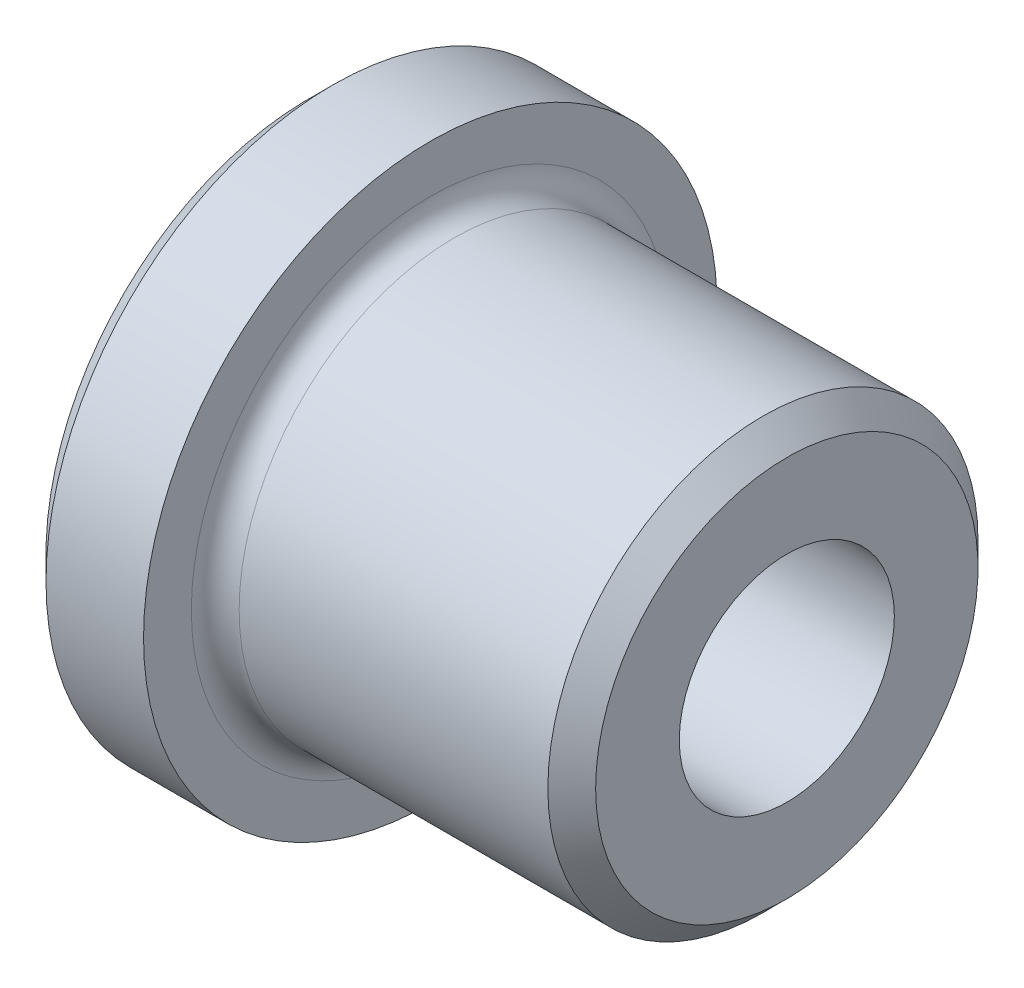
SolidWorks part; units mm, degrees
ref_plane "Piano frontale" through (0, 0, 0) normal (0, 0, 1) x (1, 0, 0)
ref_plane "Piano superiore" through (0, 0, 0) normal (0, 1, 0) x (1, 0, 0)
ref_plane "Piano destro" through (0, 0, 0) normal (1, 0, 0) x (0, 0, -1)
sketch "Sketch1" plane through (0, 0, 0) normal (0, 0, 1) x (1, 0, 0)
  line L1 (0, 2.25) -> (0, 6)
  line L2 (0, 6) -> (2.5407, 6)
  line L3 (2.5407, 6) -> (2.5407, 4.5)
  line L4 (2.5407, 4.5) -> (10, 4.5)
  line L5 (10, 4.5) -> (10, 2.25)
  line L6 (0, 2.25) -> (10, 2.25)
  line L7 (-1.7435, 0) -> (12.9506, 0) construction
revolve "Revolve1" add sketch "Sketch1" angle 360 about L7
chamfer "Chamfer1" distance 0.5 angle 45 2 edges at (10, 0, 4.5) (0, 0, 6)
fillet "Fillet1" radius 0.5 1 edges at (2.5407, 0, 4.5)
